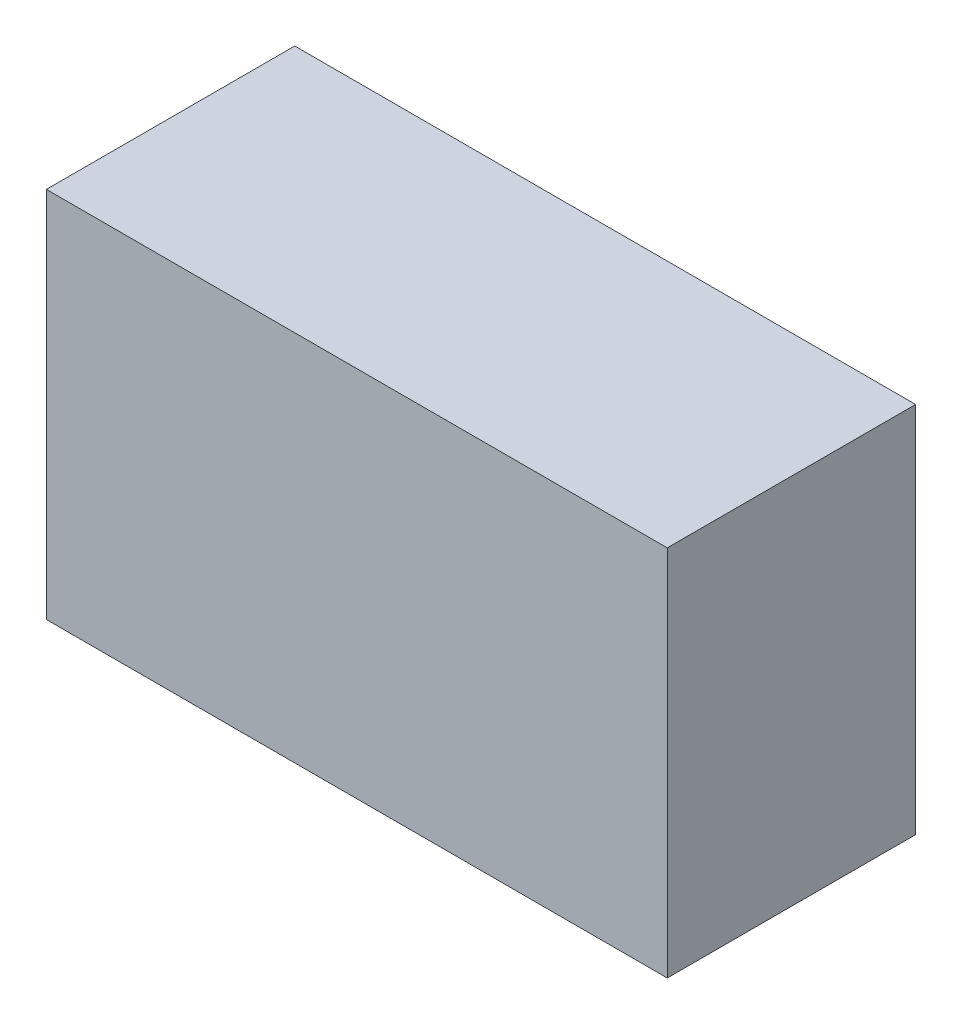
SolidWorks part; units mm, degrees
ref_plane "前视基准面" through (0, 0, 0) normal (0, 0, 1) x (1, 0, 0)
ref_plane "上视基准面" through (0, 0, 0) normal (0, 1, 0) x (1, 0, 0)
ref_plane "右视基准面" through (0, 0, 0) normal (1, 0, 0) x (0, 0, -1)
sketch "草图1" plane through (0, 0, 0) normal (0, 0, 1) x (1, 0, 0)
  line L1 (-4.1875, 11.1562) -> (20.8125, 11.1562)
  line L2 (-4.1875, 11.1562) -> (-4.1875, -3.8438)
  line L3 (-4.1875, -3.8438) -> (20.8125, -3.8438)
  line L4 (20.8125, 11.1562) -> (20.8125, -3.8438)
  dimension "D1" = 15
  dimension "D2" = 25
extrude "凸台-拉伸1" add sketch "草图1" along normal blind 10
scale "缩放比例1" bodies to scale 101 scale about centroid uniform scaling yes scale factor 0.1
